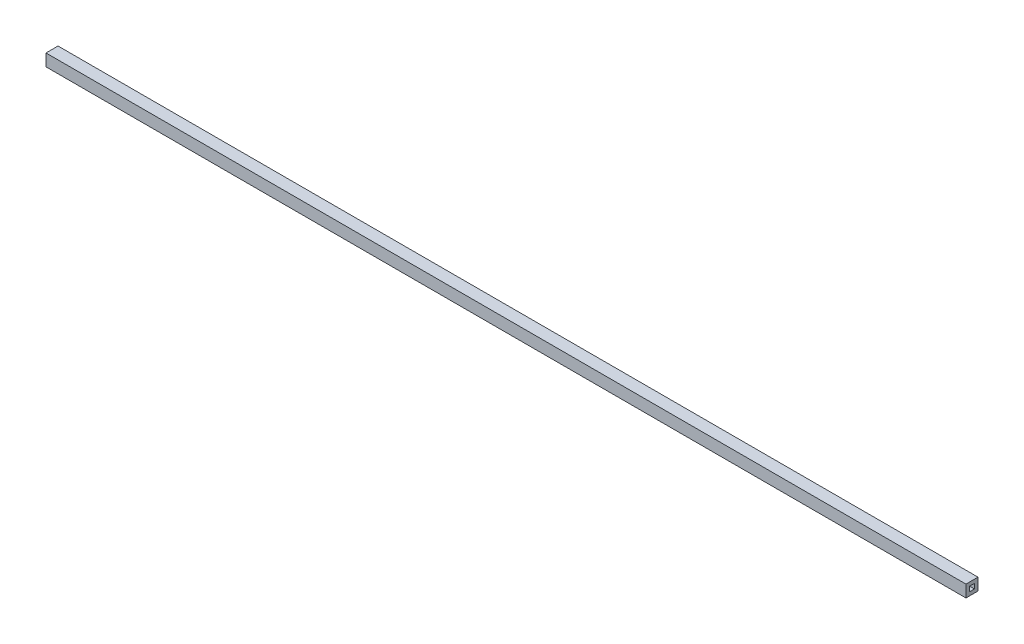
SolidWorks part; units mm, degrees
material "7075-T6 (SN)"
ref_plane "Front Plane" through (0, 0, 0) normal (0, 0, 1) x (1, 0, 0)
ref_plane "Top Plane" through (0, 0, 0) normal (0, 1, 0) x (1, 0, 0)
ref_plane "Right Plane" through (0, 0, 0) normal (1, 0, 0) x (0, 0, -1)
sketch "Sketch1" plane through (0, 0, 0) normal (1, 0, 0) x (0, 0, -1)
  line L1 (-2.5, 2.5) -> (2.5, 2.5)
  line L2 (-2.5, 2.5) -> (-2.5, -2.5)
  line L3 (-2.5, -2.5) -> (2.5, -2.5)
  line L4 (2.5, 2.5) -> (2.5, -2.5)
  line L5 (-2.5, 2.5) -> (2.5, -2.5) construction
  line L6 (-2.5, -2.5) -> (2.5, 2.5) construction
  line L7 (-1, 1) -> (1, 1)
  line L8 (-1, 1) -> (-1, -1)
  line L9 (-1, -1) -> (1, -1)
  line L10 (1, 1) -> (1, -1)
  line L11 (-1, 1) -> (1, -1) construction
  line L12 (-1, -1) -> (1, 1) construction
  point P0 (0, 0)
  point P6 (0, 0)
  dimension "D1" = 5
  dimension "D2" = 1.5
extrude "Boss-Extrude1" add sketch "Sketch1" along normal blind 382
